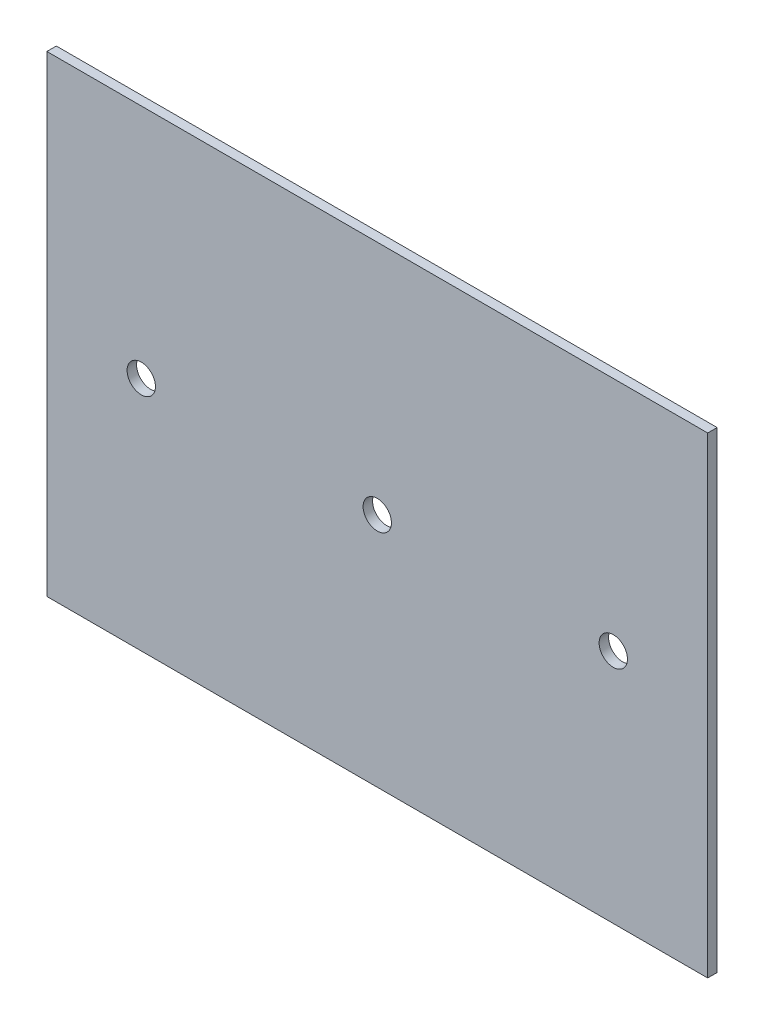
SolidWorks part; units mm, degrees
ref_plane "Alzado" through (0, 0, 0) normal (0, 0, 1) x (1, 0, 0)
ref_plane "Planta" through (0, 0, 0) normal (0, 1, 0) x (1, 0, 0)
ref_plane "Vista lateral" through (0, 0, 0) normal (1, 0, 0) x (0, 0, -1)
sketch "Croquis1" plane through (0, 0, 0) normal (0, 0, 1) x (1, 0, 0)
  line L1 (-35, -25) -> (35, -25)
  line L2 (-35, -25) -> (-35, 25)
  line L3 (-35, 25) -> (35, 25)
  line L4 (35, -25) -> (35, 25)
  line L5 (-35, -25) -> (35, 25) construction
  line L6 (-35, 25) -> (35, -25) construction
  point P0 (0, 0)
extrude "Saliente-Extruir1" add sketch "Croquis1" along normal blind 1
sketch "Croquis2" plane through (0, 0, 0) normal (0, 0, -1) x (-1, 0, 0)
  line L0 (35, 25) -> (35, -25) construction
  line L1 (-35, -25) -> (-35, 25) construction
  circle A0 centre (-25, 0) radius 1.5
  circle A1 centre (0, 0) radius 1.5
  circle A2 centre (25, 0) radius 1.5
  point P9 (-35, 0)
  dimension "D1" = 10
  dimension "D2" = 10
extrude "Cortar-Extruir1" cut sketch "Croquis2" against normal up to surface (1 mm away) up to face at (0, 0, 1)
